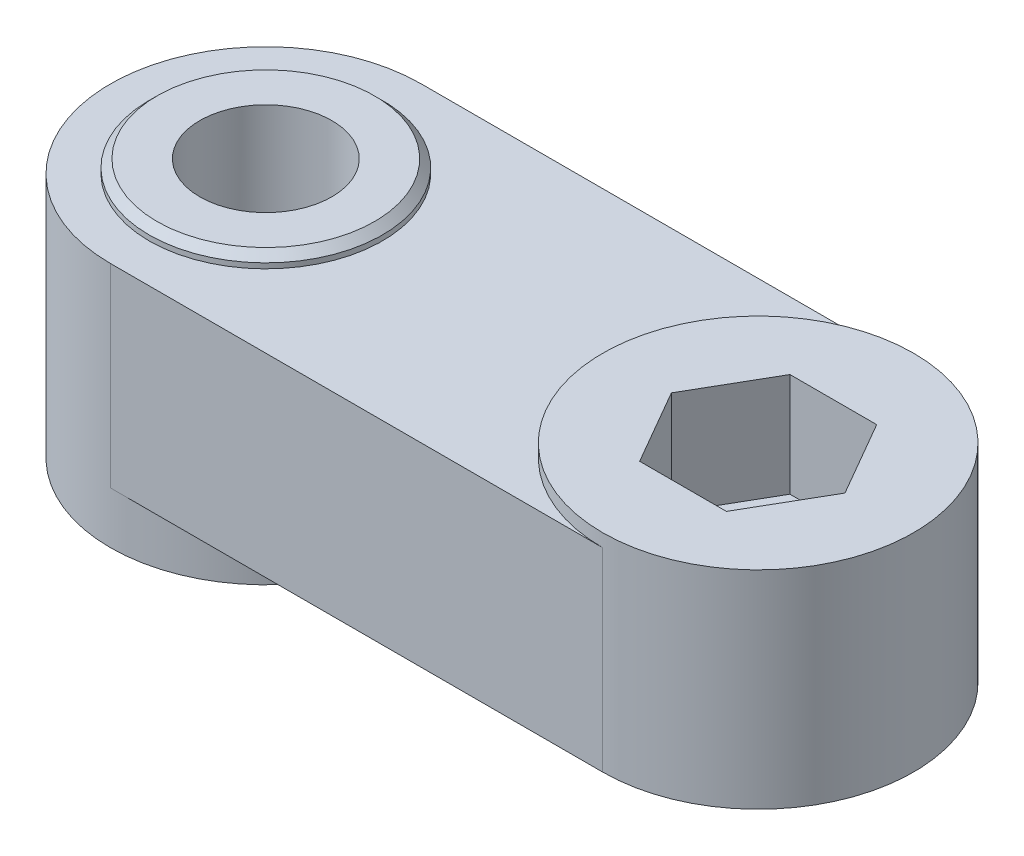
SolidWorks part; units mm, degrees
material "POM 乙缩醛共聚物"
ref_plane "前视基准面" through (0, 0, 0) normal (0, 0, 1) x (1, 0, 0)
ref_plane "上视基准面" through (0, 0, 0) normal (0, 1, 0) x (1, 0, 0)
ref_plane "右视基准面" through (0, 0, 0) normal (1, 0, 0) x (0, 0, -1)
sketch "草图1" plane through (0, 0, 0) normal (0, 1, 0) x (1, 0, 0)
  line L0 (0, 0) -> (19, 0) construction
  line L1 (0, 6) -> (19, 6)
  line L2 (0, -6) -> (19, -6)
  arc A0 (0, 6) -> (0, -6) centre (0, 0) ccw
  arc A1 (19, -6) -> (19, 6) centre (19, 0) ccw
  point P2 (9.5, 0)
  dimension "D1" = 12
  dimension "D2" = 19
extrude "凸台-拉伸1" add sketch "草图1" along normal blind 10
sketch "草图3" plane through (0, 0, 0) normal (0, 0, 1) x (1, 0, 0)
  line L0 (0, 10) -> (0, 0) construction
  line L1 (0, 10) -> (-2.55, 10)
  line L2 (0, 10) -> (-6, 10) construction
  line L3 (-2.55, 10) -> (-2.55, 5)
  line L4 (-2.55, 5) -> (-2.1, 5)
  line L5 (-2.1, 5) -> (-2.1, 2)
  line L6 (-2.1, 2) -> (-2.55, 2)
  line L7 (-2.55, 2) -> (-2.55, 0)
  line L8 (-6, 0) -> (0, 0) construction
  line L9 (-2.55, 0) -> (0, 0)
  line L10 (0, 10) -> (0, 0)
  dimension "D1" = 5.1
  dimension "D2" = 5
  dimension "D3" = 3
  dimension "D4" = 4.2
revolve "切除-旋转2" cut sketch "草图3" angle 360 about L0
sketch "草图4" plane through (0, 0, 0) normal (0, 0, 1) x (1, 0, 0)
  line L0 (19, 10) -> (19, 0) construction
  line L1 (19, 10) -> (16.5, 10)
  line L2 (0, 10) -> (19, 10) construction
  line L3 (16.5, 10) -> (16.5, 5)
  line L4 (16.5, 5) -> (16.925, 5)
  line L5 (16.925, 5) -> (16.925, 0)
  line L6 (0, 0) -> (19, 0) construction
  line L7 (16.925, 0) -> (19, 0)
  line L8 (19, 10) -> (19, 0)
  dimension "D1" = 5
  dimension "D2" = 5
  dimension "D3" = 4.15
revolve "切除-旋转3" cut sketch "草图4" angle 360 about L0
sketch "草图5" plane through (0, 0, 0) normal (0, -1, 0) x (1, 0, 0)
  line L0 (0, 6) -> (19, 6) construction
  line L1 (-4.2147, 0) -> (-2.1073, -3.65)
  line L2 (-2.1073, -3.65) -> (2.1073, -3.65)
  line L3 (2.1073, -3.65) -> (4.2147, 0)
  line L4 (4.2147, 0) -> (2.1073, 3.65)
  line L5 (2.1073, 3.65) -> (-2.1073, 3.65)
  line L6 (-2.1073, 3.65) -> (-4.2147, 0)
  circle A0 centre (0, 0) radius 3.65 construction
  dimension "D1" = 7.3
extrude "切除-拉伸1" cut sketch "草图5" against normal blind 5
sketch "草图6" plane through (0, 0, 0) normal (0, -1, 0) x (1, 0, 0)
  circle A0 centre (0, 0) radius 27.318
  circle A1 centre (0, 0) radius 6
  arc A2 (0, 6) -> (0, -6) centre (0, 0) ccw construction
extrude "切除-拉伸2" cut sketch "草图6" against normal blind 2
sketch "草图7" plane through (0, 10, 0) normal (0, 1, 0) x (1, 0, 0)
  line L0 (0, -6) -> (19, -6) construction
  line L1 (17.3257, 2.9) -> (15.6514, 0)
  line L2 (15.6514, 0) -> (17.3257, -2.9)
  line L3 (17.3257, -2.9) -> (20.6743, -2.9)
  line L4 (20.6743, -2.9) -> (22.3486, 0)
  line L5 (22.3486, 0) -> (20.6743, 2.9)
  line L6 (20.6743, 2.9) -> (17.3257, 2.9)
  circle A0 centre (19, 0) radius 2.9 construction
  dimension "D1" = 5.8
extrude "切除-拉伸3" cut sketch "草图7" against normal blind 4
sketch "草图8" plane through (0, 10, 0) normal (0, 1, 0) x (1, 0, 0)
  line L1 (-8.9825, 8.456) -> (27.2922, 8.456)
  line L2 (-8.9825, 8.456) -> (-8.9825, -8.318)
  line L3 (-8.9825, -8.318) -> (27.2922, -8.318)
  line L4 (27.2922, 8.456) -> (27.2922, -8.318)
  circle A0 centre (0, 0) radius 6
  circle A1 centre (19, 0) radius 6
  arc A2 (0, 6) -> (0, -6) centre (0, 0) ccw construction
  arc A3 (19, -6) -> (19, 6) centre (19, 0) ccw construction
extrude "切除-拉伸4" cut sketch "草图8" against normal blind 0.5
sketch "草图9" plane through (0, 10, 0) normal (0, 1, 0) x (1, 0, 0)
  circle A0 centre (0, 0) radius 4.5
  circle A1 centre (0, 0) radius 6
  circle A2 centre (0, 0) radius 6
  dimension "D1" = 0
  dimension "D2" = 1.5
extrude "切除-拉伸5" cut sketch "草图9" against normal up to surface (0.5 mm away) up to face at (9.5, 9.5, 0)
chamfer "倒角1" distance 0.3 angle 45 1 edges at (0, 10, 4.5)
